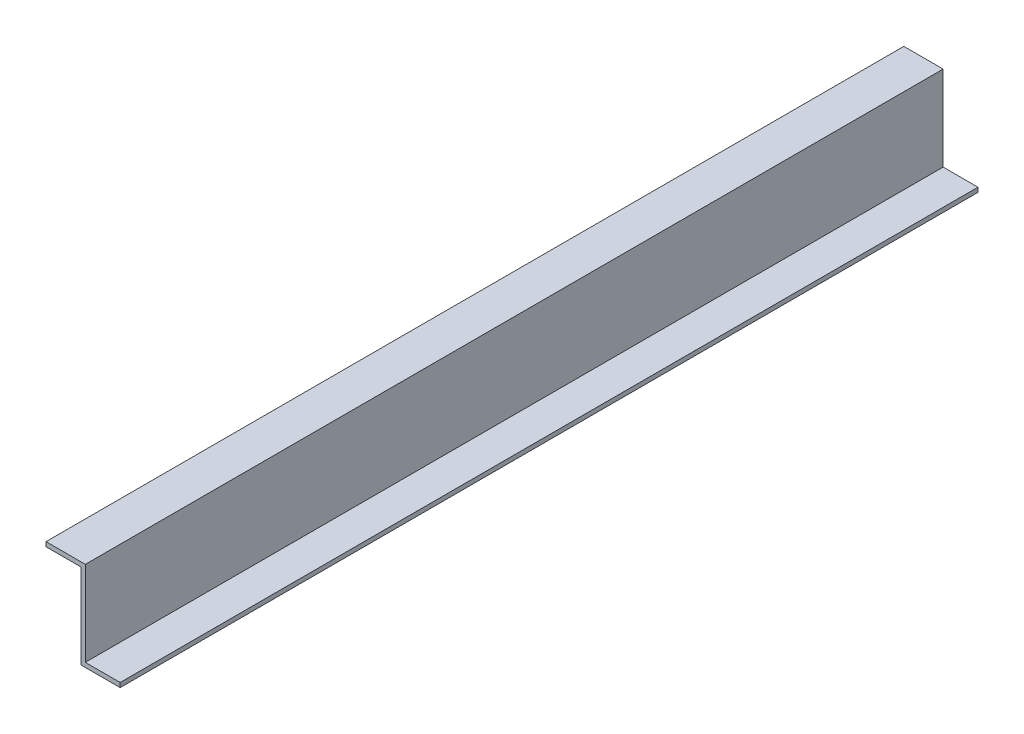
SolidWorks part; units mm, degrees
ref_plane "Front Plane" through (0, 0, 0) normal (0, 0, 1) x (1, 0, 0)
ref_plane "Top Plane" through (0, 0, 0) normal (0, 1, 0) x (1, 0, 0)
ref_plane "Right Plane" through (0, 0, 0) normal (1, 0, 0) x (0, 0, -1)
sketch "Sketch1" plane through (0, 0, 0) normal (0, 0, 1) x (1, 0, 0)
  line L0 (0, -15.0813) -> (0, 15.0813) construction
  line L1 (0, 15.0813) -> (-13.1763, 15.0813) construction
  line L2 (0, -15.0813) -> (13.1763, -15.0813) construction
  line L3 (0.7937, -14.2875) -> (13.1763, -14.2875) construction
  line L4 (0.7937, -14.2875) -> (0.7937, 15.875) construction
  line L5 (0.7937, 15.875) -> (-13.1763, 15.875) construction
  line L6 (-0.7937, -15.875) -> (13.1763, -15.875) construction
  line L7 (-0.7937, -15.875) -> (-0.7937, 14.2875) construction
  line L8 (-0.7937, 14.2875) -> (-13.1763, 14.2875) construction
  line L9 (-13.1763, 15.875) -> (-13.1763, 14.2875) construction
  line L10 (13.1763, -14.2875) -> (13.1763, -15.875) construction
  line L11 (0, 15.0813) -> (-13.1763, 15.0813) construction
  point P4 (0, 0)
  point P14 (-30.9563, 15.0813)
  point P16 (-30.9563, 15.0813)
  point P17 (-18.3632, 15.875)
  point P18 (-30.9563, 15.0813)
  point P19 (-18.7895, 15.0813)
  point P20 (0, 0)
  point P21 (-18.3632, 15.0813)
  dimension "Outside Height" = 31.75
  dimension "Wall Thickness" = 1.5875
sketch "Sketch2" plane through (0, 0, 0) normal (1, 0, 0) x (0, 0, -1)
  line L0 (152.4, 0) -> (-152.4, 0) construction
  line L1 (0, 0) -> (0, 15.875) construction
  line L2 (-152.4, 0) -> (-152.4, 15.875) construction
  line L3 (152.4, 0) -> (152.4, 15.875) construction
  point P0 (-114.3, 0)
  point P3 (114.3, 0)
  point P4 (0, 0)
  dimension "D1" = 228.6
  dimension "Length" = 304.8
sketch "Sketch3" plane through (0, 0, 0) normal (0, 0, 1) x (1, 0, 0)
  line L0 (13.1763, -14.2875) -> (13.1763, -15.875) construction
  line L1 (0.7937, -14.2875) -> (13.1763, -14.2875) construction
  line L2 (-0.7937, -15.875) -> (13.1763, -15.875) construction
  line L3 (-0.7937, -15.875) -> (-0.7937, 14.2875) construction
  line L4 (0.7937, -14.2875) -> (0.7937, 15.875) construction
  line L5 (0.7937, 15.875) -> (-13.1763, 15.875) construction
  line L6 (-13.1763, 15.875) -> (-13.1763, 14.2875) construction
  line L7 (-0.7937, 14.2875) -> (-13.1763, 14.2875) construction
  line L8 (13.1763, -14.2875) -> (13.1763, -15.875)
  line L9 (0.7937, -14.2875) -> (13.1763, -14.2875)
  line L10 (-0.7937, -15.875) -> (13.1763, -15.875)
  line L11 (-0.7937, -15.875) -> (-0.7937, 14.2875)
  line L12 (0.7937, -14.2875) -> (0.7937, 15.875)
  line L13 (0.7937, 15.875) -> (-13.1763, 15.875)
  line L14 (-13.1763, 15.875) -> (-13.1763, 14.2875)
  line L15 (-0.7937, 14.2875) -> (-13.1763, 14.2875)
extrude "Boss-Extrude1" add sketch "Sketch3" along normal up to vertex (152.4 mm away) and the other way up to vertex (152.4 mm away) up to point (0, 0, 152.4) other way up to point (0, 0, -152.4)
equation "\"D1@Sketch2\"=\"Length@Sketch2\"*0.75"
